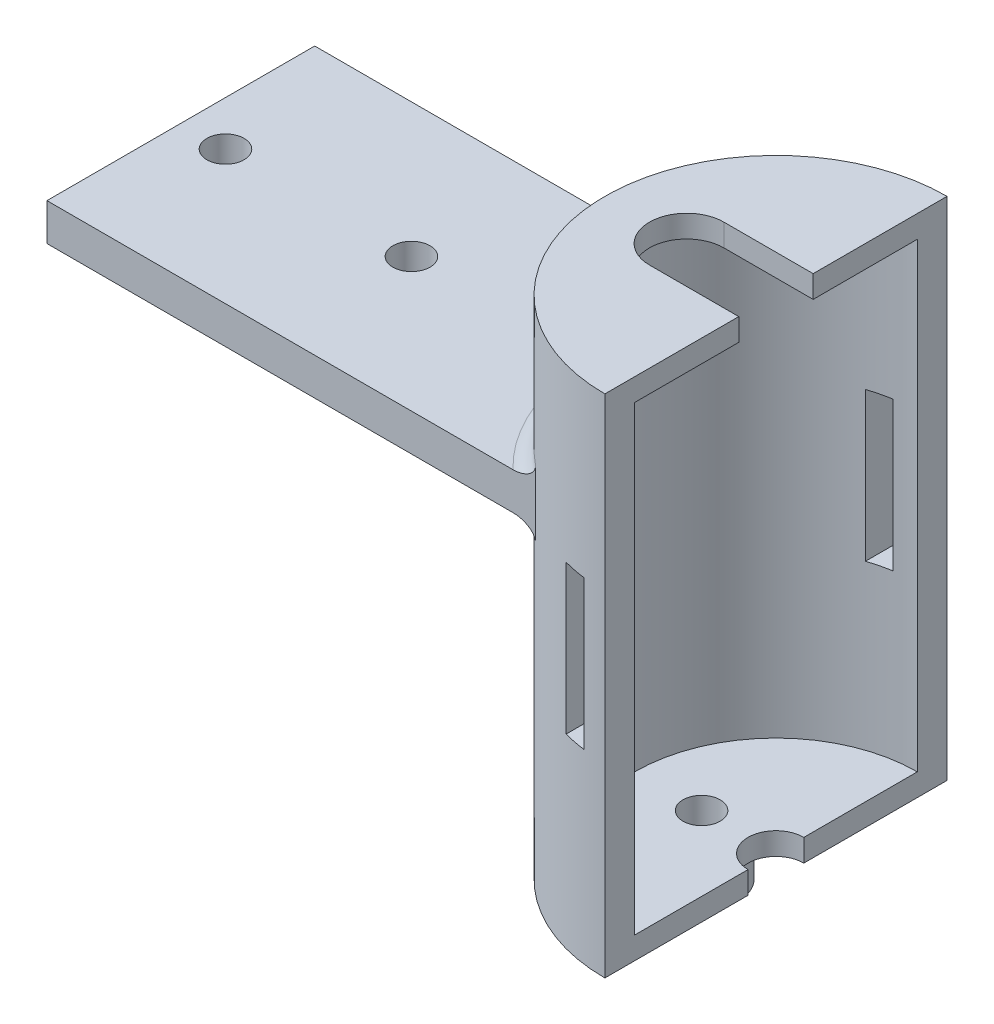
SolidWorks part; units mm, degrees
ref_plane "Front Plane" through (0, 0, 0) normal (0, 0, 1) x (1, 0, 0)
ref_plane "Top Plane" through (0, 0, 0) normal (0, 1, 0) x (1, 0, 0)
ref_plane "Right Plane" through (0, 0, 0) normal (1, 0, 0) x (0, 0, -1)
sketch "Sketch1" plane through (0, 0, 0) normal (0, 1, 0) x (1, 0, 0)
  line L0 (0, 23) -> (0, 19)
  line L1 (0, -19) -> (0, -23)
  arc A0 (0, 19) -> (0, -19) centre (0, 0) ccw
  arc A1 (0, 23) -> (0, -23) centre (0, 0) ccw
  dimension "D1" = 38
  dimension "D2" = 46
extrude "Boss-Extrude1" add sketch "Sketch1" along normal blind 62
sketch "Sketch3" plane through (0, 0, 0) normal (0, -1, 0) x (1, 0, 0)
  line L0 (0, 23) -> (0, 3.75)
  line L1 (0, -3.75) -> (0, -23)
  arc A0 (0, 23) -> (0, -23) centre (0, 0) ccw construction
  arc A1 (0, 23) -> (0, -23) centre (0, 0) ccw
  arc A2 (0, 3.75) -> (0, -3.75) centre (0, 0) ccw
  dimension "D1" = 7.5
extrude "Boss-Extrude2" add sketch "Sketch3" along normal blind 3
sketch "Sketch4" plane through (0, -3, 0) normal (0, -1, 0) x (1, 0, 0)
  line L0 (0, 3.75) -> (0, 23) construction
  circle A0 centre (-10, 0) radius 5
  dimension "D1" = 10
  dimension "D2" = 10
extrude "Boss-Extrude3" add sketch "Sketch4" along normal blind 5
hole_wizard "M6x1.0 Tapped Hole1" positions "Sketch7" profile "Sketch6" tap size "M6x1.0" standard "Ansi Metric" end condition through all
sketch "Sketch7" plane through (0, -8, 0) normal (0, -1, 0) x (1, 0, 0)
  circle A0 centre (-10, 0) radius 5 construction
  point P0 (-10, 0)
sketch "Sketch6" plane through (-10, -8, 0) normal (1, 0, 0) x (0, 0, -1)
  line L0 (0, 0) -> (0, 70)
  line L1 (0, 70) -> (2.5, 70)
  line L2 (2.5, 70) -> (2.5, 0)
  line L5 (2.5, 0) -> (0, 0)
  line L11 (0, -6.35) -> (0, 107.95) construction
  dimension "Thru Tap Drill Dia." = 5
  dimension "Thru Tap Drill Depth" = 70
cosmetic thread "Hole Thread1" parameters "D2"=6
sketch "Sketch8" plane through (0, 0, 0) normal (0, 0, 1) x (1, 0, 0)
  line L0 (0, 62) -> (0, -3) construction
  line L1 (-6, 42) -> (-3, 42)
  line L2 (-6, 42) -> (-6, 22)
  line L3 (-6, 22) -> (-3, 22)
  line L4 (-3, 42) -> (-3, 22)
  line L6 (0, 62) -> (-23, 62) construction
  dimension "D1" = 3
  dimension "D2" = 3
  dimension "D3" = 20
  dimension "D4" = 20
extrude "Cut-Extrude1" cut sketch "Sketch8" against normal through all and the other way through all
sketch "Sketch9" plane through (0, 62, 0) normal (0, 1, 0) x (1, 0, 0)
  line L0 (0, -23) -> (0, 23)
  arc A0 (0, 23) -> (0, -23) centre (0, 0) ccw construction
  arc A1 (0, 23) -> (0, -23) centre (0, 0) ccw
extrude "Boss-Extrude4" add sketch "Sketch9" along normal blind 3
sketch "Sketch10" plane through (0, 65, 0) normal (0, 1, 0) x (1, 0, 0)
  line L0 (0, 0) -> (-12, 0) construction
  line L1 (0, -23) -> (0, 23) construction
  line L2 (0, -5) -> (-12, -5)
  line L3 (0, 5) -> (-12, 5)
  arc A0 (0, -5) -> (0, 5) centre (0, 0) ccw
  arc A1 (-12, 5) -> (-12, -5) centre (-12, 0) ccw
  point P4 (-6, 0)
  dimension "D1" = 12
  dimension "D2" = 10
extrude "Cut-Extrude2" cut sketch "Sketch10" against normal up to next
ref_plane "Plane2" through (0, 40, 0) normal (0, 1, 0) x (-1, 0, 0)
sketch "Sketch11" plane through (0, 40, 0) normal (0, 1, 0) x (-1, 0, 0)
  line L0 (14.3178, 18) -> (80, 18)
  line L1 (14.3178, -18) -> (80, -18)
  line L2 (10, 0) -> (56.9076, 0) construction
  line L3 (80, 18) -> (80, -18)
  line L4 (49, 0) -> (74, 0) construction
  arc A0 (0, -23) -> (0, 23) centre (0, 0) ccw construction
  arc A1 (14.3178, -18) -> (14.3178, 18) centre (0, 0) ccw
  circle A2 centre (49, 0) radius 2.5
  circle A3 centre (74, 0) radius 2.5
  point P12 (55, 0)
  dimension "D4" = 5
  dimension "D1" = 18
  dimension "D2" = 18
  dimension "D3" = 80
  dimension "D5" = 6
  dimension "D6" = 25
extrude "Boss-Extrude5" add sketch "Sketch11" along normal blind 5
sketch "Sketch12" plane through (0, 0, 18) normal (0, 0, 1) x (1, 0, 0)
  line L0 (-14.3178, 40) -> (-14.3178, 60)
  line L1 (-14.3178, 45) -> (-14.3178, 40) construction
  line L2 (-14.3178, 60) -> (-80, 45)
  line L3 (-80, 40) -> (-14.3178, 40) construction
  line L4 (-80, 40) -> (-14.3178, 40)
  line L5 (-80, 45) -> (-80, 40) construction
  line L6 (-80, 45) -> (-80, 40)
  dimension "D1" = 20
extrude "Boss-Extrude7" [suppressed] add sketch "Sketch12" against normal blind 3
mirror "Mirror1" [suppressed] about plane through (0, 0, 0) normal (0, 0, 1)
fillet "Fillet1" radius 2 2 edges at (-23, 40, 0) (-23, 45, 0)
